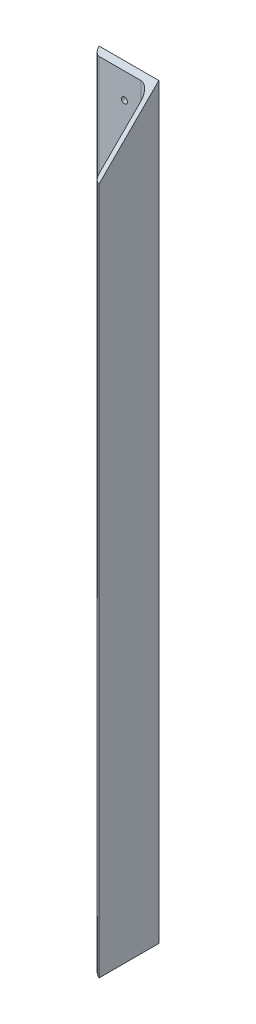
SolidWorks part; units mm, degrees
ref_plane "Front Plane" through (0, 0, 0) normal (0, 0, 1) x (1, 0, 0)
ref_plane "Top Plane" through (0, 0, 0) normal (0, 1, 0) x (1, 0, 0)
ref_plane "Right Plane" through (0, 0, 0) normal (1, 0, 0) x (0, 0, -1)
sketch "Sketch1" plane through (0, 0, 0) normal (0, 0, 1) x (1, 0, 0)
  line L0 (0, 0) -> (0, 500)
  dimension "D1" = 500
other "L angle (equal) 40X40X3(1)"
ref_plane "Plane1" through (0, 0, 0) normal (0, 1, 0) x (-1, 0, 0)
sketch "Sketch11" plane through (0, 0, 0) normal (0, 1, 0) x (-1, 0, 0)
  line L0 (0, 40) -> (0, 0)
  line L2 (3, 37) -> (3, 9)
  line L3 (9, 3) -> (37, 3)
  line L5 (40, 0) -> (0, 0)
  arc A0 (3, 37) -> (0, 40) centre (0, 37) ccw
  arc A1 (40, 0) -> (37, 3) centre (37, 0) ccw
  arc A2 (9, 3) -> (3, 9) centre (9, 9) cw
  point P8 (0, 20)
  point P9 (20, 0)
  point P10 (0, 0)
  dimension "Radius_2" = 3
  dimension "Radius_1" = 6
  dimension "V_leg" = 40
  dimension "H_leg" = 40
  dimension "thickness" = 3
sketch "Sketch12" plane through (0, 0, 0) normal (1, 0, 0) x (0, 0, -1)
  line L0 (-40, 500) -> (0, 500)
  line L1 (0, 500) -> (-40, 460)
  line L4 (-40, 0) -> (0, 0)
  line L5 (0, 0) -> (0, 500)
  line L6 (0, 500) -> (-40, 500)
  line L7 (-40, 500) -> (-40, 0)
  line L8 (-40, 0) -> (0, 0)
  line L10 (0, 500) -> (-40, 500) construction
  line L11 (-40, 500) -> (-40, 460)
  line M7 (0, 500) -> (-40, 500)
  line M8 (-40, 500) -> (-40, 0)
  dimension "D1" = 0
extrude "Cut-Extrude1" cut sketch "Sketch12" against normal through all contours L1 M7 M8
sketch "Sketch14" plane through (0, 0, 0) normal (0, 0, -1) x (-1, 0, 0)
  line L0 (0, 0) -> (40, 40)
  line L4 (0, 0) -> (40, 0)
  line L5 (40, 0) -> (40, 500)
  line L6 (40, 500) -> (0, 500)
  line L7 (0, 500) -> (0, 0)
  line L8 (0, 0) -> (40, 0)
  line L9 (40, 0) -> (40, 40)
  line L13 (40, 500) -> (0, 500)
  line M5 (0, 0) -> (40, 0)
  line M6 (40, 0) -> (40, 500)
  dimension "D1" = 0
extrude "Cut-Extrude2" cut sketch "Sketch14" against normal through all contours L0 M5 M6
ref_plane "Plane2" through (0, 250, -250) normal (0, 0.7071, -0.7071) x (-1, 0, 0)
ref_plane "Plane3" through (0, 0, 0) normal (0.7071, -0.7071, 0) x (0, 0, -1)
ref_plane "Plane4" through (0, 0, 0) normal (0, 0, -1) x (-1, 0, 0)
sketch "Sketch16" plane through (0, 0, 0) normal (0, 0, -1) x (-1, 0, 0)
  line L0 (40, 480) -> (0, 480) construction
  line L1 (40, 20) -> (0, 20) construction
  line L4 (0, 0) -> (40, 40)
  line L5 (40, 40) -> (40, 500)
  line L6 (40, 500) -> (0, 500)
  line L7 (0, 500) -> (0, 0)
  line L8 (0, 0) -> (40, 40) construction
  line L9 (40, 40) -> (40, 500) construction
  line L10 (40, 500) -> (0, 500) construction
  line L11 (0, 500) -> (0, 0) construction
  circle A0 centre (20, 480) radius 2
  circle A1 centre (20, 20) radius 2
  dimension "D2" = 4
  dimension "D1" = 0
extrude "Cut-Extrude3" cut sketch "Sketch16" against normal blind 10
